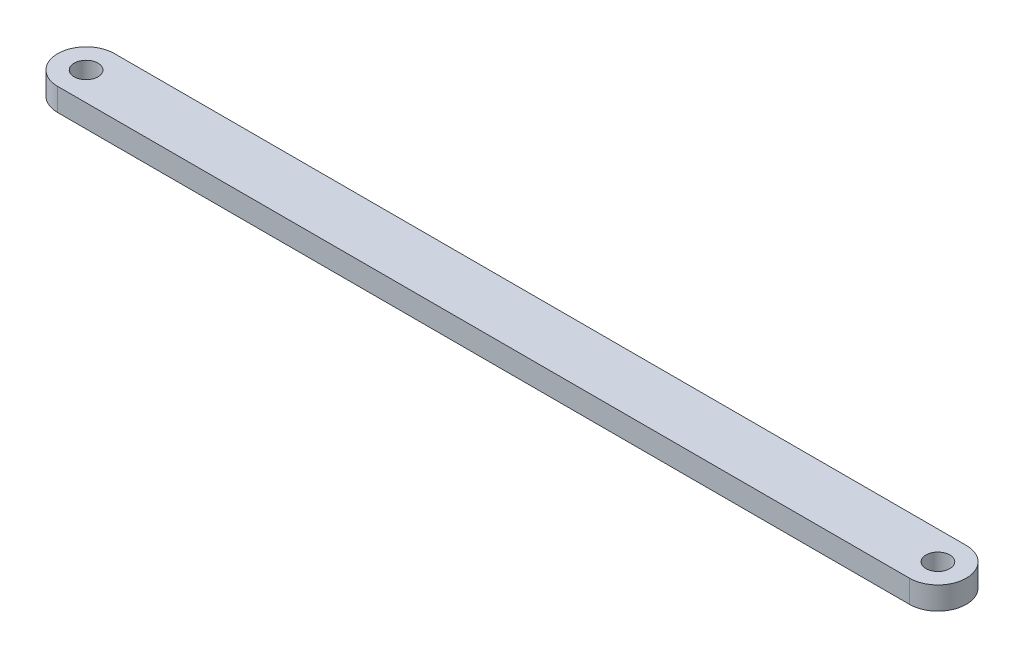
SolidWorks part; units mm, degrees
ref_plane "Front Plane" through (0, 0, 0) normal (0, 0, 1) x (1, 0, 0)
ref_plane "Top Plane" through (0, 0, 0) normal (0, 1, 0) x (1, 0, 0)
ref_plane "Right Plane" through (0, 0, 0) normal (1, 0, 0) x (0, 0, -1)
sketch "Sketch1" plane through (0, 0, 0) normal (0, 1, 0) x (1, 0, 0)
  line L0 (0, 0) -> (75, 0) construction
  line L1 (0, 2.5) -> (75, 2.5)
  line L2 (0, -2.5) -> (75, -2.5)
  arc A0 (0, 2.5) -> (0, -2.5) centre (0, 0) ccw
  arc A1 (75, -2.5) -> (75, 2.5) centre (75, 0) ccw
  circle A2 centre (0, 0) radius 1.05
  circle A3 centre (75, 0) radius 1.05
  point P3 (37.5, 0)
  dimension "D2" = 2.5
  dimension "D4" = 2.1
  dimension "D5" = 2.1
  dimension "D1" = 75
extrude "Boss-Extrude1" add sketch "Sketch1" along normal blind 2
